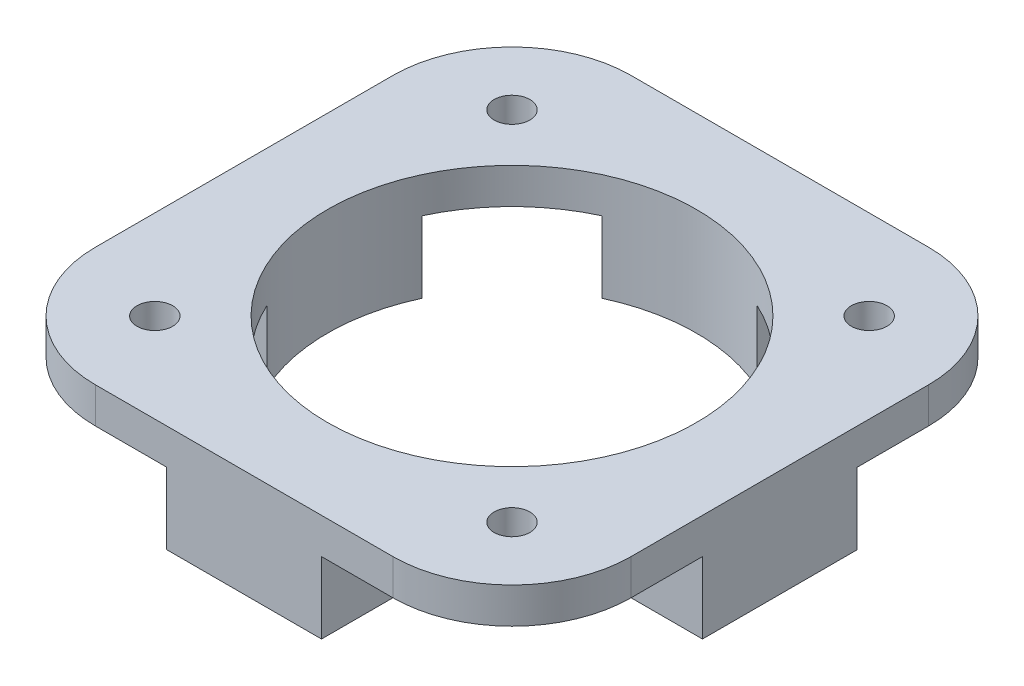
SolidWorks part; units mm, degrees
ref_plane "Front Plane" through (0, 0, 0) normal (0, 0, 1) x (1, 0, 0)
ref_plane "Top Plane" through (0, 0, 0) normal (0, 1, 0) x (1, 0, 0)
ref_plane "Right Plane" through (0, 0, 0) normal (1, 0, 0) x (0, 0, -1)
sketch "Sketch1" plane through (0, 0, 0) normal (0, 1, 0) x (1, 0, 0)
  line L0 (0.4983, 20.5642) -> (0.4983, -20.3884) construction
  line L5 (-21.2761, -0.4983) -> (21.0166, -0.4983) construction
  line L6 (12.9983, -22.9983) -> (-12.0017, -22.9983)
  line L7 (22.9983, -12.9983) -> (22.9983, 12.0017)
  line L8 (12.9983, 22.0017) -> (-12.0017, 22.0017)
  line L9 (-22.0017, -12.9983) -> (-22.0017, 12.0017)
  line L10 (22.9983, -22.9983) -> (-22.0017, 22.0017) construction
  line L11 (22.9983, 22.0017) -> (-22.0017, -22.9983) construction
  circle A0 centre (-14.5017, 14.5017) radius 1.5
  circle A1 centre (15.4983, 14.5017) radius 1.5
  circle A2 centre (15.4983, -15.4983) radius 1.5
  circle A3 centre (-14.5017, -15.4983) radius 1.5
  arc A4 (22.9983, 12.0017) -> (12.9983, 22.0017) centre (12.9983, 12.0017) ccw
  arc A5 (12.9983, -22.9983) -> (22.9983, -12.9983) centre (12.9983, -12.9983) ccw
  arc A6 (-12.0017, -22.9983) -> (-22.0017, -12.9983) centre (-12.0017, -12.9983) cw
  arc A7 (-12.0017, 22.0017) -> (-22.0017, 12.0017) centre (-12.0017, 12.0017) ccw
  point P0 (0.4983, -0.4983)
  dimension "D1" = 3
  dimension "D4" = 10
  dimension "D2" = 45
  dimension "D3" = 45
extrude "Boss-Extrude1" add sketch "Sketch1" along normal blind 3
sketch "Sketch2" plane through (0, 0, 0) normal (0, 1, 0) x (1, 0, 0)
  line L0 (12.9983, 22.0017) -> (-12.0017, 22.0017) construction
  line L9 (22.9983, -12.9983) -> (22.9983, 12.0017) construction
  line L14 (-12.0017, -22.9983) -> (12.9983, -22.9983) construction
  line L19 (-22.0017, 12.0017) -> (-22.0017, -12.9983) construction
  line L24 (-6, 22.0017) -> (-6, 6)
  line L25 (-6, 6) -> (-22.0017, 6)
  line L26 (-22.0017, -6.9983) -> (-6.0017, -6.9983)
  line L27 (-6.0017, -6.9983) -> (-6.0017, -22.9983)
  line L28 (6.9983, -22.9983) -> (6.9983, -6.9983)
  line L29 (6.9983, -6.9983) -> (22.9983, -6.9983)
  line L30 (22.9983, 6) -> (6.9983, 6)
  line L31 (6.9983, 6) -> (6.9983, 22.0017)
  line L32 (-22.0017, 6) -> (-22.0017, -6.9983)
  line L33 (-6, 22.0017) -> (6.9983, 22.0017)
  line L34 (22.9983, 6) -> (22.9983, -6.9983)
  line L35 (6.9983, -22.9983) -> (-6.0017, -22.9983)
  circle A0 centre (-14.5017, -15.4983) radius 1.5 construction
  circle A1 centre (15.4983, -15.4983) radius 1.5 construction
  circle A2 centre (15.4983, 14.5017) radius 1.5 construction
  circle A3 centre (-14.5017, 14.5017) radius 1.5 construction
  dimension "D5" = 8.5
  dimension "D7" = 8.5017
  dimension "D1" = 8.5
  dimension "D2" = 8.5
  dimension "D3" = 8.5
  dimension "D4" = 8.5017
  dimension "D6" = 8.5017
  dimension "D8" = 8.5
extrude "Boss-Extrude2" add sketch "Sketch2" against normal blind 6
sketch "Sketch3" plane through (0, 0, 0) normal (0, 1, 0) x (1, 0, 0)
  circle A0 centre (0.4983, -0.4983) radius 15.5
extrude "Cut-Extrude1" cut sketch "Sketch3" along normal mid plane 15
